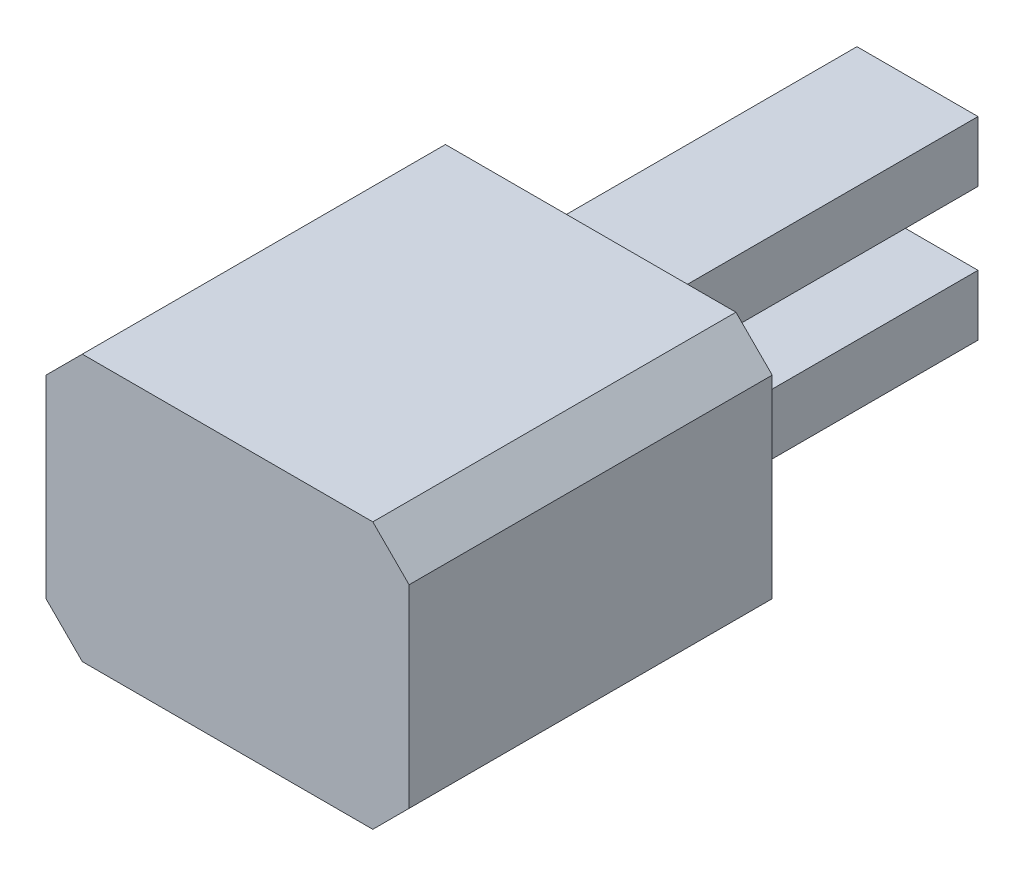
SolidWorks part; units mm, degrees
ref_plane "Front Plane" through (0, 0, 0) normal (0, 0, 1) x (1, 0, 0)
ref_plane "Top Plane" through (0, 0, 0) normal (0, 1, 0) x (1, 0, 0)
ref_plane "Right Plane" through (0, 0, 0) normal (1, 0, 0) x (0, 0, -1)
ref_plane "PL_Body_base" through (0, 0, -66) normal (0, 0, 1) x (1, 0, 0)
sketch "SK_Body" plane through (0, 0, -66) normal (0, 0, 1) x (1, 0, 0)
  line L0 (-24, -22) -> (24, -22)
  line L1 (24, -22) -> (30, -16)
  line L2 (30, -16) -> (30, 16)
  line L3 (30, 16) -> (24, 22)
  line L4 (24, 22) -> (-24, 22)
  line L5 (-24, 22) -> (-30, 16)
  line L6 (-30, 16) -> (-30, -16)
  line L7 (-30, -16) -> (-24, -22)
  dimension "P1" = 24
  dimension "P2" = 22
  dimension "P3" = 24
  dimension "P4" = 22
  dimension "P5" = 30
  dimension "P6" = 16
  dimension "P7" = 30
  dimension "P8" = 16
  dimension "P9" = 24
  dimension "P10" = 22
  dimension "P11" = 24
  dimension "P12" = 22
  dimension "P13" = 30
  dimension "P14" = 16
  dimension "P15" = 30
  dimension "P16" = 16
extrude "Body" add sketch "SK_Body" along normal blind 60
ref_plane "PL_Finger_A_base" through (0, 0, -120) normal (0, 0, 1) x (1, 0, 0)
sketch "SK_Finger_A" plane through (0, 0, -120) normal (0, 0, 1) x (1, 0, 0)
  line L0 (-10, 6) -> (10, 6)
  line L1 (10, 6) -> (10, 16)
  line L2 (10, 16) -> (-10, 16)
  line L3 (-10, 16) -> (-10, 6)
  dimension "P1" = 10
  dimension "P2" = 6
  dimension "P3" = 10
  dimension "P4" = 6
  dimension "P5" = 10
  dimension "P6" = 16
  dimension "P7" = 10
  dimension "P8" = 16
extrude "Finger_A" add sketch "SK_Finger_A" along normal blind 54
ref_plane "PL_Finger_B_base" through (0, 0, -120) normal (0, 0, 1) x (1, 0, 0)
sketch "SK_Finger_B" plane through (0, 0, -120) normal (0, 0, 1) x (1, 0, 0)
  line L0 (-10, -16) -> (10, -16)
  line L1 (10, -16) -> (10, -6)
  line L2 (10, -6) -> (-10, -6)
  line L3 (-10, -6) -> (-10, -16)
  dimension "P1" = 10
  dimension "P2" = 16
  dimension "P3" = 10
  dimension "P4" = 16
  dimension "P5" = 10
  dimension "P6" = 6
  dimension "P7" = 10
  dimension "P8" = 6
extrude "Finger_B" add sketch "SK_Finger_B" along normal blind 54
